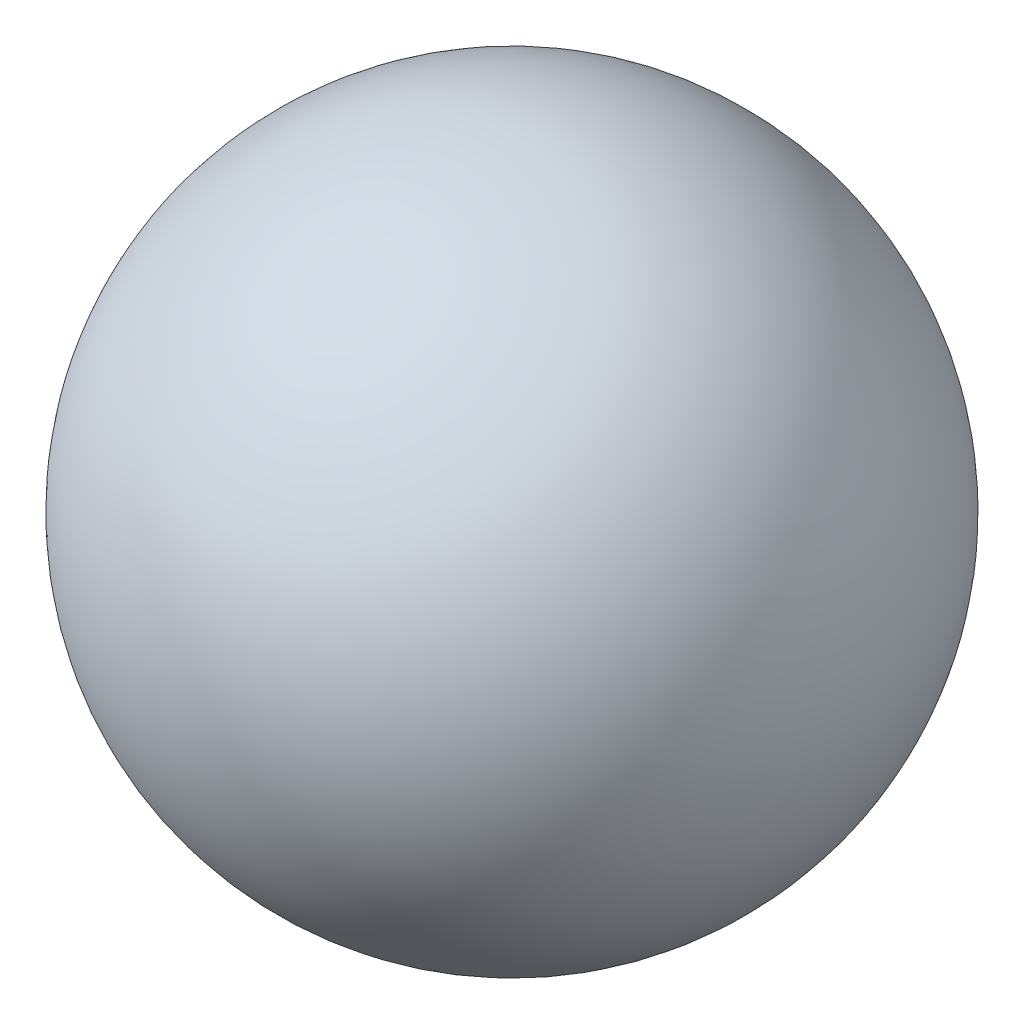
SolidWorks part; units mm, degrees
ref_plane "Front Plane" through (0, 0, 0) normal (0, 0, 1) x (1, 0, 0)
ref_plane "Top Plane" through (0, 0, 0) normal (0, 1, 0) x (1, 0, 0)
ref_plane "Right Plane" through (0, 0, 0) normal (1, 0, 0) x (0, 0, -1)
sketch "Sketch1" plane through (0, 0, 0) normal (0, 0, 1) x (1, 0, 0)
  line L0 (-4.76, 0) -> (4.76, 0)
  arc A0 (-4.76, 0) -> (4.76, 0) centre (0, 0) cw
  dimension "D2" = 4.76
  dimension "D1" = 9.52
revolve "Revolve1" add sketch "Sketch1" angle 360 about L0
